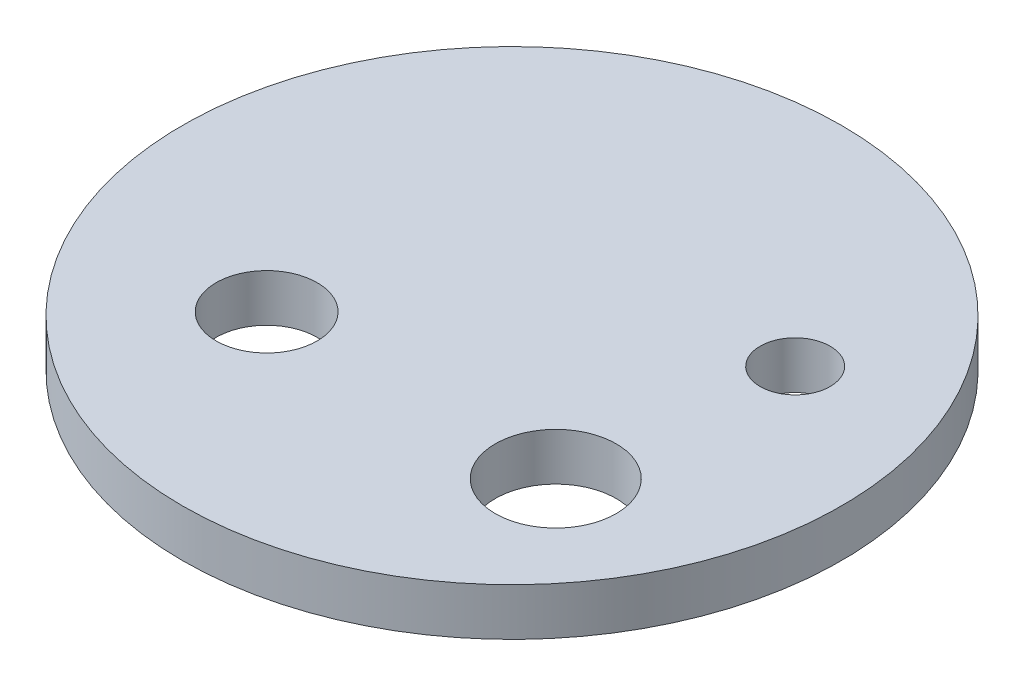
SolidWorks part; units mm, degrees
ref_plane "Front Plane" through (0, 0, 0) normal (0, 0, 1) x (1, 0, 0)
ref_plane "Top Plane" through (0, 0, 0) normal (0, 1, 0) x (1, 0, 0)
ref_plane "Right Plane" through (0, 0, 0) normal (1, 0, 0) x (0, 0, -1)
sketch "Sketch1" plane through (0, 0, 0) normal (0, 1, 0) x (1, 0, 0)
  circle A0 centre (0, 0) radius 69.5131
  circle A1 centre (39.1288, 20.598) radius 7.3828
  circle A2 centre (34.4039, -25.1754) radius 12.7584
  circle A3 centre (-26.5781, -25.1754) radius 10.6579
extrude "Boss-Extrude1" add sketch "Sketch1" along normal blind 10
